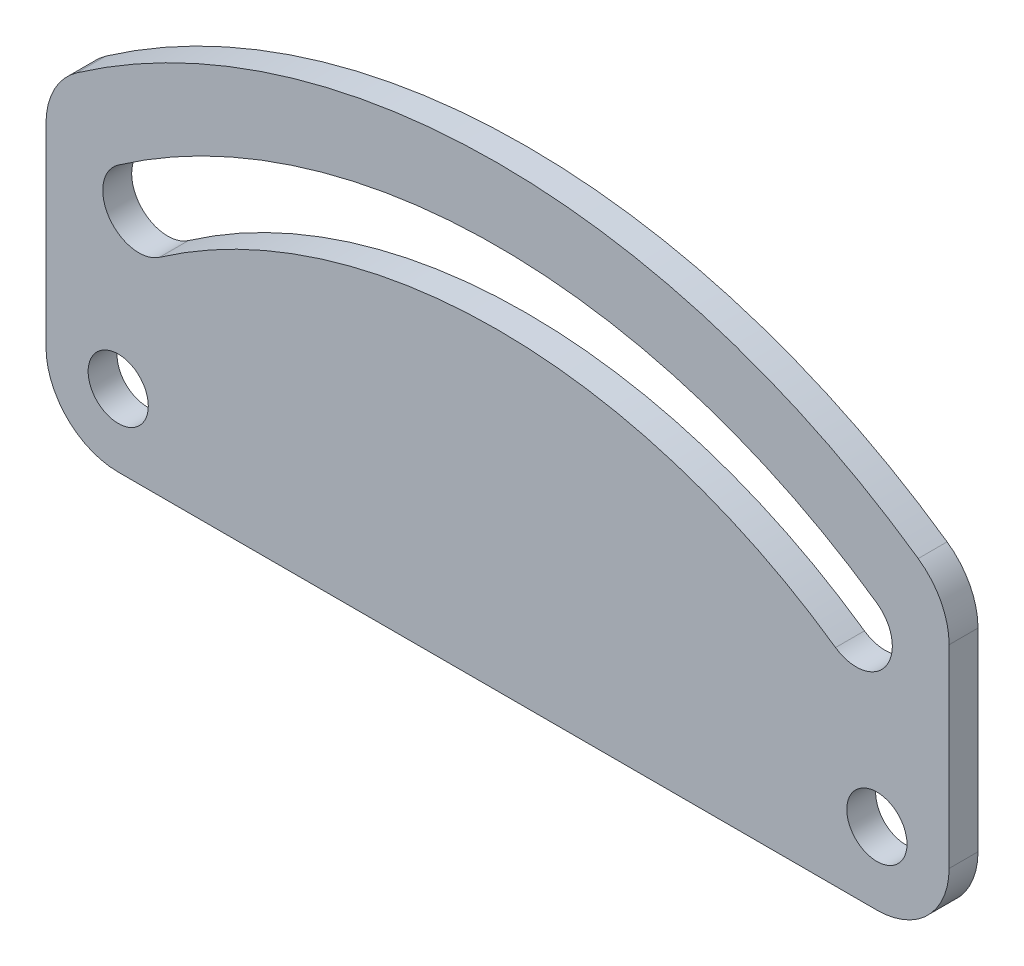
SolidWorks part; units mm, degrees
ref_plane "Front Plane" through (0, 0, 0) normal (0, 0, 1) x (1, 0, 0)
ref_plane "Top Plane" through (0, 0, 0) normal (0, 1, 0) x (1, 0, 0)
ref_plane "Right Plane" through (0, 0, 0) normal (1, 0, 0) x (0, 0, -1)
sketch "Sketch1" plane through (0, 0, 0) normal (0, 0, 1) x (1, 0, 0)
  line L0 (0, 23.3845) -> (0, 6.35)
  line L1 (6.35, 0) -> (73.0572, 0)
  line L2 (79.4072, 6.35) -> (79.4072, 23.3845)
  line L3 (39.7036, 40.2235) -> (39.7036, 0) construction
  arc A0 (2.7156, 28.5915) -> (76.6917, 28.5915) centre (39.7036, -24.4009) cw
  arc A1 (79.4072, 23.3845) -> (76.6917, 28.5915) centre (73.0572, 23.3845) ccw
  arc A2 (0, 23.3845) -> (2.7156, 28.5915) centre (6.35, 23.3845) cw
  arc A3 (73.0572, 0) -> (79.4072, 6.35) centre (73.0572, 6.35) ccw
  arc A4 (0, 6.35) -> (6.35, 0) centre (6.35, 6.35) ccw
  arc A5 (6.35, 23.3845) -> (73.0572, 23.3845) centre (39.7036, -24.4009) cw
  arc A6 (9.9844, 18.1774) -> (69.4228, 18.1774) centre (39.7036, -24.4009) cw
  arc A7 (69.4228, 18.1774) -> (73.0572, 23.3845) centre (71.24, 20.781) ccw
  arc A8 (9.9844, 18.1774) -> (6.35, 23.3845) centre (8.1672, 20.781) cw
  circle A9 centre (6.35, 6.35) radius 2.6455
  circle A10 centre (73.0572, 6.35) radius 2.6455
  point P14 (0, 0)
  dimension "D1" = 6.35
  dimension "D2" = 6.35
  dimension "D3" = 6.35
  dimension "D4" = 6.35
extrude "Boss-Extrude1" add sketch "Sketch1" against normal blind 2.54 contours L3 A0 A2 L0 A4 L1 A6 A8 A5 A9 | A0 L3 A5 A7 A6 L1 A3 L2 A1 A10
